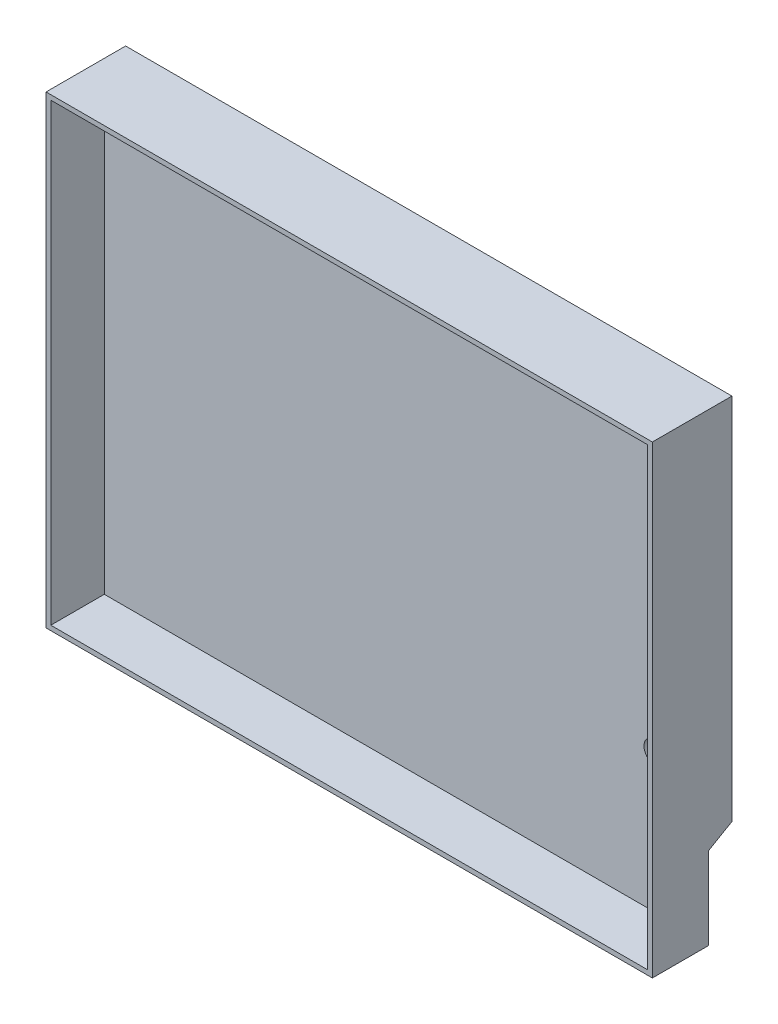
SolidWorks part; units mm, degrees
other "Marca1"
sketch "Croquis3" plane through (-73.6845, -67.0046, 0) normal (-0.0818, -0.6716, -0.7364) x (0.9966, -0.0614, -0.0547)
other "Marca2"
sketch "Croquis6" plane through (-73.6845, -68.0046, 11.8) normal (0, 0, 1) x (1, 0, 0)
ref_plane "Alzado" through (0, 0, 0) normal (0, 0, 1) x (1, 0, 0)
ref_plane "Planta" through (0, 0, 0) normal (0, 1, 0) x (1, 0, 0)
ref_plane "Vista lateral" through (0, 0, 0) normal (1, 0, 0) x (0, 0, -1)
sketch "Croquis1" plane through (0, 0, 0) normal (0, 0, 1) x (1, 0, 0)
  line L0 (-73.6845, 29.9954) -> (54.3155, 29.9954)
  line L1 (54.3155, 29.9954) -> (54.3155, -68.0046)
  line L2 (54.3155, -68.0046) -> (-73.6845, -68.0046)
  line L3 (-73.6845, -68.0046) -> (-73.6845, 29.9954)
  dimension "D1" = 128
  dimension "D2" = 98
extrude "Saliente-Extruir1" add sketch "Croquis1" along normal blind 11.8
sketch "Croquis2" plane through (0, 0, 11.8) normal (0, 0, 1) x (1, 0, 0)
  line L0 (-72.6845, 28.9954) -> (-72.6845, -67.0046)
  line L1 (-72.6845, -67.0046) -> (53.3155, -67.0046)
  line L2 (53.3155, -67.0046) -> (53.3155, 28.9954)
  line L3 (53.3155, 28.9954) -> (-72.6845, 28.9954)
  line L4 (54.3155, 29.9954) -> (-73.6845, 29.9954) construction
  line L5 (-73.6845, -68.0046) -> (54.3155, -68.0046) construction
  line L6 (-73.6845, 29.9954) -> (-73.6845, -68.0046) construction
  dimension "D1" = 1
  dimension "D2" = 1
  dimension "D3" = 1
  dimension "D4" = 126
extrude "Cortar-Extruir1" cut sketch "Croquis2" against normal blind 11.3
sketch "Croquis5" plane through (-73.6845, 0, 0) normal (-1, 0, 0) x (0, 0, 1)
  line L0 (0, -68.0046) -> (0, -50.6846) construction
  line L1 (0, 29.9954) -> (0, -68.0046) construction
  line L2 (0, -50.6846) -> (-4.997, -47.7996)
  line L3 (11.8, -68.0046) -> (0, -68.0046) construction
  line L4 (-4.997, -47.7996) -> (-4.997, 29.9954)
  line L5 (-4.997, 29.9954) -> (0, 29.9954)
  line L6 (0, 29.9954) -> (0, -50.6846)
  dimension "D1" = 17.32
  dimension "D2" = 5.77
  dimension "D3" = 30
extrude "Saliente-Extruir2" add sketch "Croquis5" against normal blind 128
sketch "Croquis7" plane through (0, 0, -4.997) normal (0, 0, -1) x (-1, 0, 0)
  line L0 (-54.3155, -47.7996) -> (-45.0155, -47.7996) construction
  line L1 (-54.3155, -47.7996) -> (73.6845, -47.7996) construction
  line L2 (-45.0155, -47.7996) -> (-45.0155, -38.7996) construction
  circle A0 centre (-43.7511, -37.7679) radius 2.5
extrude "Cortar-Extruir2" cut sketch "Croquis7" against normal blind 22 contours A0
